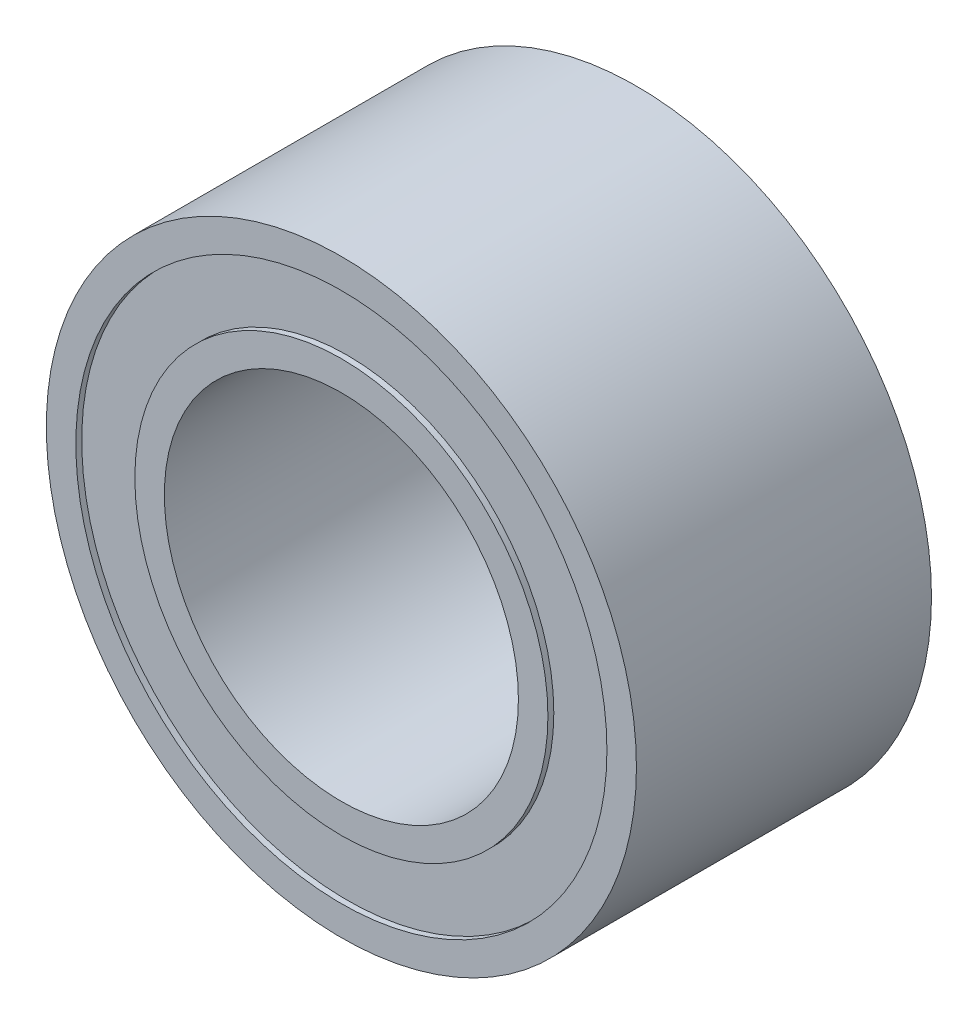
SolidWorks part; units mm, degrees
ref_plane "Front Plane" through (0, 0, 0) normal (0, 0, 1) x (1, 0, 0)
ref_plane "Top Plane" through (0, 0, 0) normal (0, 1, 0) x (1, 0, 0)
ref_plane "Right Plane" through (0, 0, 0) normal (1, 0, 0) x (0, 0, -1)
sketch "Sketch1" plane through (0, 0, 0) normal (0, 0, 1) x (1, 0, 0)
  circle A2 centre (0, 0) radius 7.62
  circle A3 centre (0, 0) radius 12.7
  dimension "D1" = 15.24
  dimension "D2" = 25.4
extrude "Boss-Extrude1" add sketch "Sketch1" along normal blind 12.7
sketch "Sketch2" plane through (0, 0, 12.7) normal (0, 0, 1) x (1, 0, 0)
  circle A0 centre (0, 0) radius 7.62 construction
  circle A1 centre (0, 0) radius 7.62
  circle A2 centre (0, 0) radius 11.43
  circle A3 centre (0, 0) radius 8.89
  dimension "D1" = 22.86
  dimension "D2" = 17.78
extrude "Cut-Extrude1" cut sketch "Sketch2" against normal blind 0.254 contours A2 A3
ref_plane "Plane1" through (0, 0, 6.35) normal (0, 0, 1) x (1, 0, 0)
mirror "Mirror1" about plane through (0, 0, 6.35) normal (0, 0, 1) of "Cut-Extrude1"
equation "\"Shaftdia\"=0.6"
equation "\"D1@Sketch1\"=\"Shaftdia\""
equation "\"D2@Sketch1\"=\"Shaftdia\"+0.4in"
equation "\"D1@Sketch2\"=\"Shaftdia\"+0.3in"
equation "\"D2@Sketch2\"=\"Shaftdia\"+0.1"
